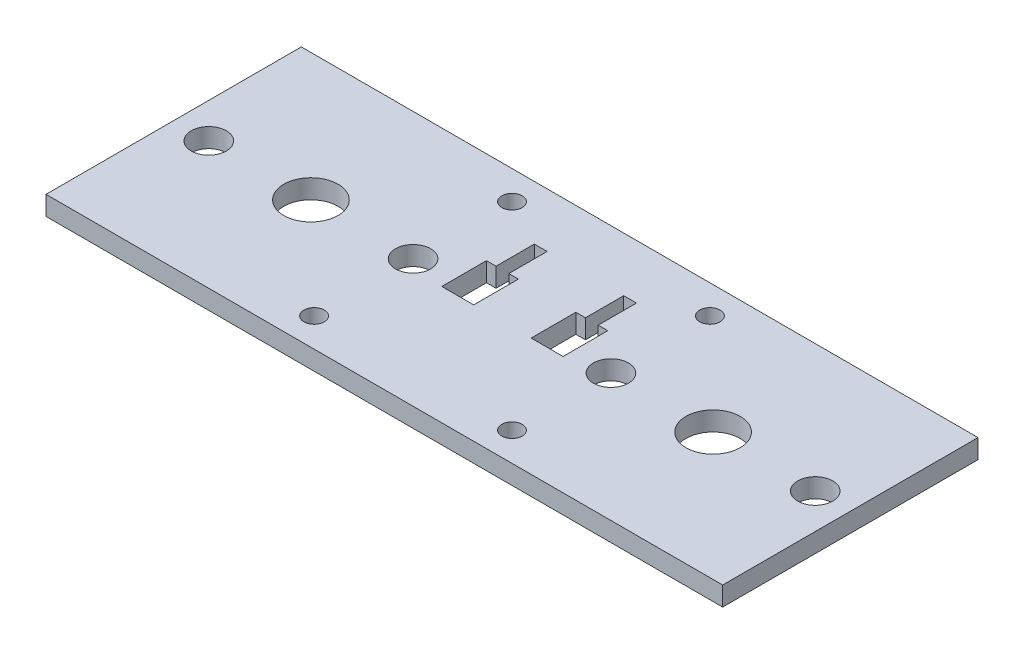
SolidWorks part; units mm, degrees
ref_plane "前视基准面" through (0, 0, 0) normal (0, 0, 1) x (1, 0, 0)
ref_plane "上视基准面" through (0, 0, 0) normal (0, 1, 0) x (1, 0, 0)
ref_plane "右视基准面" through (0, 0, 0) normal (1, 0, 0) x (0, 0, -1)
sketch "草图1" plane through (0, 0, 0) normal (0, 1, 0) x (1, 0, 0)
  line L2 (-53, 20) -> (-53, -20)
  line L3 (-53, -20) -> (53, -20)
  line L4 (53, 20) -> (53, -20)
  line L5 (-53, 20) -> (53, -20) construction
  line L6 (-53, -20) -> (53, 20) construction
  line L11 (-53, 20) -> (53, 20)
  point P0 (0, 0)
  dimension "D1" = 106
  dimension "D2" = 40
extrude "凸台-拉伸1" add sketch "草图1" along normal blind 3
sketch "草图2" plane through (0, 3, 0) normal (0, 1, 0) x (1, 0, 0)
  line L0 (0, -1000) -> (0, 49000) construction
  line L2 (-1031.5, 0) -> (48968.5, 0) construction
  line L3 (-31.5, -995) -> (-31.5, 49005) construction
  line L4 (31.5, -1001) -> (31.5, 48999) construction
  circle A0 centre (-31.5, 0) radius 4.25
  circle A1 centre (31.5, 0) radius 4.25
  circle A2 centre (-47.5, 0) radius 2.75
  circle A3 centre (-15.5, 0) radius 2.75
  circle A4 centre (15.5, 0) radius 2.75
  circle A5 centre (47.5, 0) radius 2.75
  point P9 (0, 0)
  point P23 (0, 0)
  dimension "D1" = 8.5
  dimension "D4" = 5.5
  dimension "D6" = 5.5
  dimension "D2" = 63
  dimension "D5" = 32
  dimension "D7" = 32
extrude "切除-拉伸1" cut sketch "草图2" against normal up to next
sketch "草图3" plane through (0, 3, 0) normal (0, 1, 0) x (1, 0, 0)
  line L0 (-1000, 0) -> (49000, 0) construction
  line L1 (0, -1000) -> (0, 49000) construction
  circle A0 centre (-15.5, -15.5) radius 1.6
  circle A1 centre (-15.5, 15.5) radius 1.6
  circle A2 centre (15.5, 15.5) radius 1.6
  circle A3 centre (15.5, -15.5) radius 1.6
  dimension "D1" = 3.2
  dimension "D2" = 31
  dimension "D3" = 31
extrude "切除-拉伸2" cut sketch "草图3" against normal up to next
sketch "草图4" plane through (0, 3, 0) normal (0, 1, 0) x (1, 0, 0)
  line L0 (0, -1000) -> (0, 49000) construction
  line L1 (-998.5584, 8.5) -> (49001.4416, 8.5) construction
  line L2 (-6, 5.5) -> (-4.5, 5.5)
  line L3 (-8, 11.5) -> (-6, 11.5)
  line L4 (-8, 11.5) -> (-8, 5.5)
  line L6 (-6, 11.5) -> (-6, 5.5)
  line L7 (-8, 11.5) -> (-6, 5.5) construction
  line L8 (-8, 5.5) -> (-6, 11.5) construction
  line L9 (-9.5, 5.5) -> (-8, 5.5)
  line L10 (-9.5, 5.5) -> (-9.5, -1.5)
  line L11 (-9.5, -1.5) -> (-4.5, -1.5)
  line L12 (-4.5, 5.5) -> (-4.5, -1.5)
  line L13 (-9.5, 5.5) -> (-4.5, -1.5) construction
  line L14 (-9.5, -1.5) -> (-4.5, 5.5) construction
  line L15 (8, 11.5) -> (8, 5.5)
  line L16 (9.5, 5.5) -> (8, 5.5)
  line L17 (9.5, 5.5) -> (9.5, -1.5)
  line L18 (9.5, -1.5) -> (4.5, -1.5)
  line L19 (4.5, 5.5) -> (4.5, -1.5)
  line L20 (6, 5.5) -> (4.5, 5.5)
  line L21 (6, 11.5) -> (6, 5.5)
  line L22 (8, 11.5) -> (6, 11.5)
  point P4 (-7, 8.5)
  point P10 (-7, 2)
  dimension "D1" = 8.5
  dimension "D2" = 2
  dimension "D3" = 6
  dimension "D4" = 5
  dimension "D5" = 7
  dimension "D6" = 12
extrude "切除-拉伸3" cut sketch "草图4" against normal up to next
